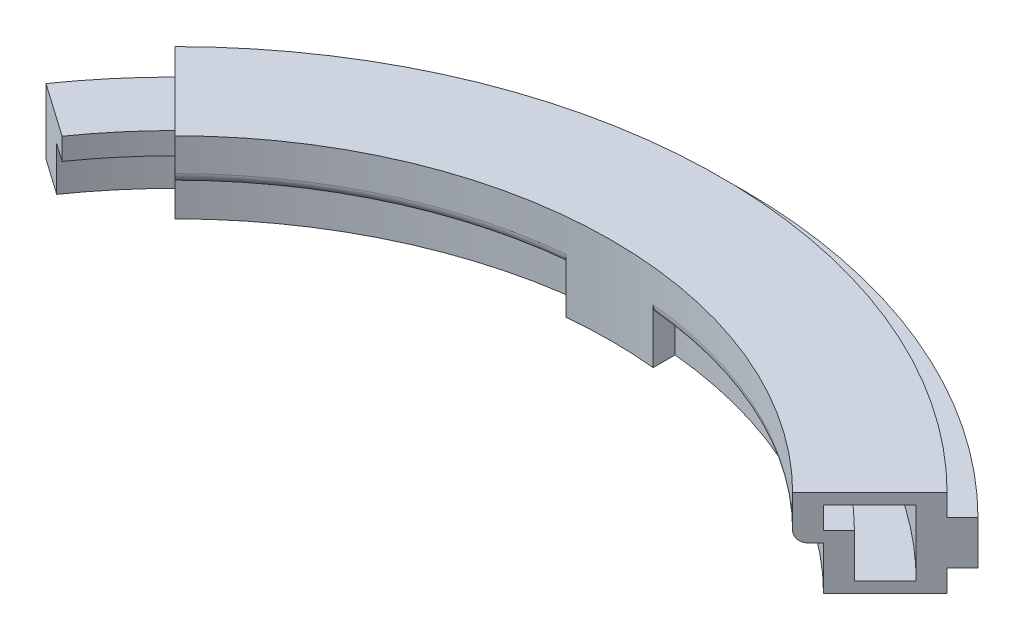
SolidWorks part; units mm, degrees
ref_plane "Front Plane" through (0, 0, 0) normal (0, 0, 1) x (1, 0, 0)
ref_plane "Top Plane" through (0, 0, 0) normal (0, 1, 0) x (1, 0, 0)
ref_plane "Right Plane" through (0, 0, 0) normal (1, 0, 0) x (0, 0, -1)
sketch "Sketch1" plane through (0, 0, 0) normal (0, 1, 0) x (1, 0, 0)
  line L0 (0, 0) -> (88.3883, 88.3883)
  line L1 (-10, 105) -> (10, 105)
  line L2 (-10, 105) -> (-10, -105)
  line L3 (-10, -105) -> (10, -105)
  line L4 (10, 105) -> (10, -105)
  line L5 (-10, 105) -> (10, -105) construction
  line L6 (-10, -105) -> (10, 105) construction
  line L7 (-105, 10) -> (105, 10)
  line L8 (-105, 10) -> (-105, -10)
  line L9 (-105, -10) -> (105, -10)
  line L10 (105, 10) -> (105, -10)
  line L11 (-105, 10) -> (105, -10) construction
  line L12 (-105, -10) -> (105, 10) construction
  line L13 (0, 0) -> (-88.3883, 88.3883)
  line L14 (0, 0) -> (0, 10) construction
  circle A0 centre (0, 0) radius 125
  arc A1 (10, 99.4987) -> (-10, 99.4987) centre (0, 0) ccw
  circle A2 centre (0, 0) radius 105
  arc A3 (-99.4987, 10) -> (-99.4987, -10) centre (0, 0) ccw
  arc A4 (-10, -99.4987) -> (10, -99.4987) centre (0, 0) ccw
  arc A5 (99.4987, -10) -> (99.4987, 10) centre (0, 0) ccw
  dimension "D1" = 250
  dimension "D2" = 200
  dimension "D3" = 210
  dimension "D4" = 20
  dimension "D5" = 20
  dimension "D6" = 90
  dimension "D7" = 45
extrude "Boss-Extrude1" add sketch "Sketch1" along normal blind 10 contours A2 L0 A0 L13 L2 L1 L4 | L4 A2 L2 A1 | A2 L4 L1 | A2 L1 L2
sketch "Sketch2" plane through (0, 10, 0) normal (0, 1, 0) x (1, 0, 0)
  line L0 (0, 0) -> (88.3883, 88.3883)
  line L1 (0, 0) -> (-88.3883, 88.3883)
  circle A0 centre (0, 0) radius 125
  circle A1 centre (0, 0) radius 100
  arc M1 (-74.2462, 74.2462) -> (-10, 104.5227) centre (0, 0) cw
  line M2 (-10, 104.5227) -> (-10, 99.4987)
  arc M3 (-10, 99.4987) -> (10, 99.4987) centre (0, 0) cw
  line M4 (10, 99.4987) -> (10, 104.5227)
  arc M5 (10, 104.5227) -> (74.2462, 74.2462) centre (0, 0) cw
  line M6 (74.2462, 74.2462) -> (88.3883, 88.3883)
  arc M7 (88.3883, 88.3883) -> (-88.3883, 88.3883) centre (0, 0) ccw
  line M8 (-88.3883, 88.3883) -> (-74.2462, 74.2462)
  dimension "D1" = 250
  dimension "D2" = 200
extrude "Boss-Extrude2" add sketch "Sketch2" along normal blind 10 contours M8 M1 M2 M3 M4 M5 M6 M7 | A1 L1 M2 M1 | A1 L0 M5 M4
sketch "Sketch3" plane through (0, 0, 0) normal (-0.7071, 0, 0.7071) x (0.7071, 0, 0.7071)
  line L0 (-125, 20) -> (-125, 0) construction
  line L1 (-120, 12.5) -> (-110, 12.5)
  line L2 (-120, 12.5) -> (-120, 2.5)
  line L3 (-120, 2.5) -> (-110, 2.5)
  line L4 (-110, 12.5) -> (-110, 2.5)
  line L5 (-120, 12.5) -> (-110, 2.5) construction
  line L6 (-120, 2.5) -> (-110, 12.5) construction
  line L7 (-120, 17.5) -> (-105, 17.5)
  line L8 (-120, 17.5) -> (-120, 12.5)
  line L9 (-120, 12.5) -> (-105, 12.5)
  line L10 (-105, 17.5) -> (-105, 12.5)
  line L11 (-120, 17.5) -> (-105, 12.5) construction
  line L12 (-120, 12.5) -> (-105, 17.5) construction
  line L13 (-125, 20) -> (-100, 20) construction
  line L14 (-105, 0) -> (-125, 0) construction
  line L15 (-105, 10) -> (-105, 0) construction
  line L17 (0, 0) -> (0, 74.964) construction
  point P0 (-115, 7.5)
  point P5 (-112.5, 15)
  dimension "D1" = 5
  dimension "D2" = 15
  dimension "D3" = 5
  dimension "D4" = 2.5
  dimension "D5" = 2.5
  dimension "D6" = 5
  dimension "D7" = 5
revolve "Revolve1" add sketch "Sketch3" angle 10 about L17
sketch "Sketch4" plane through (0, 0, 0) normal (0.7071, 0, 0.7071) x (0.7071, 0, -0.7071)
  line L0 (100, 20) -> (125, 20) construction
  line L1 (110, 12.5) -> (120, 12.5)
  line L2 (110, 12.5) -> (110, 2.5)
  line L3 (110, 2.5) -> (120, 2.5)
  line L4 (120, 12.5) -> (120, 2.5)
  line L5 (110, 12.5) -> (120, 2.5) construction
  line L6 (110, 2.5) -> (120, 12.5) construction
  line L7 (105, 17.5) -> (120, 17.5)
  line L8 (105, 17.5) -> (105, 12.5)
  line L9 (105, 12.5) -> (120, 12.5)
  line L10 (120, 17.5) -> (120, 12.5)
  line L11 (105, 17.5) -> (120, 12.5) construction
  line L12 (105, 12.5) -> (120, 17.5) construction
  line L13 (100, 20) -> (100, 10) construction
  line L14 (125, 20) -> (125, 0) construction
  line L15 (105, 10) -> (105, 0) construction
  line L16 (105, 0) -> (125, 0) construction
  line L17 (0, 0) -> (0, 64.257) construction
  point P0 (115, 7.5)
  point P5 (112.5, 15)
  dimension "D1" = 5
  dimension "D2" = 2.5
  dimension "D3" = 5
  dimension "D4" = 5
  dimension "D5" = 5
  dimension "D6" = 2.5
revolve "Cut-Revolve1" cut sketch "Sketch4" angle 12 about L17
sketch "Sketch5" plane through (0, 0, 0) normal (-0.7071, 0, 0.7071) x (0.7071, 0, 0.7071)
  line L0 (-125, 20) -> (-125, 0) construction
  line L1 (-120, 5) -> (-130, 5)
  line L2 (-120, 5) -> (-120, 15)
  line L3 (-120, 15) -> (-130, 15)
  line L4 (-130, 5) -> (-130, 15)
  line L5 (-120, 5) -> (-130, 15) construction
  line L6 (-120, 15) -> (-130, 5) construction
  line L8 (0, 0) -> (0, 48.5073) construction
  point P0 (-125, 10)
  dimension "D1" = 10
  dimension "D2" = 10
revolve "Revolve2" add sketch "Sketch5" angle 90 about L8
fillet "Fillet1" radius 2.5 2 edges at (-42.8456, 10, -90.3563) (42.8456, 10, -90.3563)
